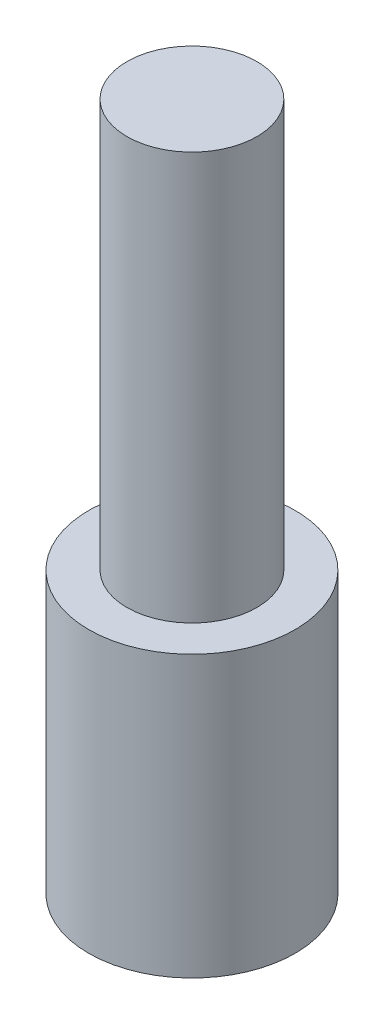
SolidWorks part; units mm, degrees
ref_plane "Front Plane" through (0, 0, 0) normal (0, 0, 1) x (1, 0, 0)
ref_plane "Top Plane" through (0, 0, 0) normal (0, 1, 0) x (1, 0, 0)
ref_plane "Right Plane" through (0, 0, 0) normal (1, 0, 0) x (0, 0, -1)
sketch "Sketch1" plane through (0, 0, 0) normal (0, 1, 0) x (1, 0, 0)
  circle A0 centre (0, 0) radius 4.05
  dimension "D1" = 8.1
extrude "Boss-Extrude1" add sketch "Sketch1" along normal blind 11
sketch "Sketch3" plane through (0, 11, 0) normal (0, 1, 0) x (1, 0, 0)
  circle A0 centre (0, 0) radius 2.55
  dimension "D1" = 5.1
extrude "Boss-Extrude2" add sketch "Sketch3" along normal blind 16
